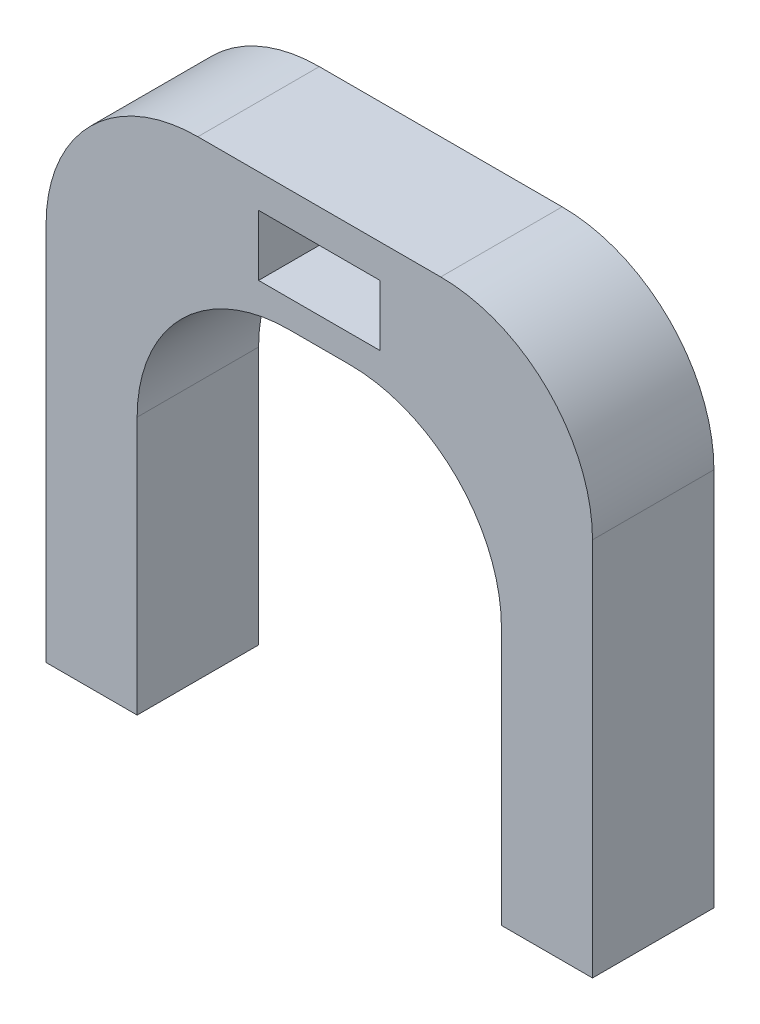
SolidWorks part; units mm, degrees
ref_plane "正面" through (0, 0, 0) normal (0, 0, 1) x (1, 0, 0)
ref_plane "平面" through (0, 0, 0) normal (0, 1, 0) x (1, 0, 0)
ref_plane "右側面" through (0, 0, 0) normal (1, 0, 0) x (0, 0, -1)
sketch "ｽｹｯﾁ2" plane through (0, 0, 0) normal (0, 0, 1) x (1, 0, 0)
  line L1 (0, 0) -> (18, 0)
  line L2 (0, 0) -> (0, 21.5)
  line L3 (0, 21.5) -> (18, 21.5)
  line L4 (18, 0) -> (18, 21.5)
  dimension "D1" = 21.5
  dimension "D2" = 18
extrude "ﾎﾞｽ - 押し出し1" add sketch "ｽｹｯﾁ2" along normal blind 4
sketch "ｽｹｯﾁ3" plane through (0, 0, 4) normal (0, 0, 1) x (1, 0, 0)
  line L0 (0, 0) -> (18, 0) construction
  line L1 (3, 0) -> (15, 0)
  line L2 (3, 0) -> (3, 17.5)
  line L3 (3, 17.5) -> (15, 17.5)
  line L4 (15, 0) -> (15, 17.5)
  line L5 (0, 21.5) -> (0, 0) construction
  line L6 (18, 0) -> (18, 21.5) construction
  line L7 (18, 21.5) -> (0, 21.5) construction
  dimension "D1" = 3
  dimension "D2" = 3
  dimension "D3" = 4
extrude "ｶｯﾄ - 押し出し1" cut sketch "ｽｹｯﾁ3" against normal through all
fillet "ﾌｨﾚｯﾄ1" radius 5 2 edges at (15, 17.5, 2) (3, 17.5, 2)
fillet "ﾌｨﾚｯﾄ2" radius 5 2 edges at (18, 21.5, 2) (0, 21.5, 2)
sketch "ｽｹｯﾁ4" plane through (0, 0, 4) normal (0, 0, 1) x (1, 0, 0)
  line L0 (0, 16.5) -> (0, 0) construction
  line L1 (7, 20.4009) -> (11, 20.4009)
  line L2 (7, 20.4009) -> (7, 18.4009)
  line L3 (7, 18.4009) -> (11, 18.4009)
  line L4 (11, 20.4009) -> (11, 18.4009)
  dimension "D1" = 2
  dimension "D2" = 4
  dimension "D3" = 7
extrude "ｶｯﾄ - 押し出し2" cut sketch "ｽｹｯﾁ4" against normal through all
sketch "ｽｹｯﾁ8" plane through (0, 0, 4) normal (0, 0, 1) x (1, 0, 0)
  line L0 (3, 12.5) -> (3, 0) construction
  line L1 (0, 0) -> (3, 0)
  line L2 (0, 0) -> (0, 4)
  line L3 (0, 4) -> (3, 4)
  line L4 (3, 0) -> (3, 4)
  line L5 (18, 0) -> (18, 16.5) construction
  line L6 (15, 0) -> (18, 0)
  line L7 (15, 0) -> (15, 4)
  line L8 (15, 4) -> (18, 4)
  line L9 (18, 0) -> (18, 4)
  dimension "D1" = 4
extrude "ｶｯﾄ - 押し出し5" cut sketch "ｽｹｯﾁ8" against normal through all
